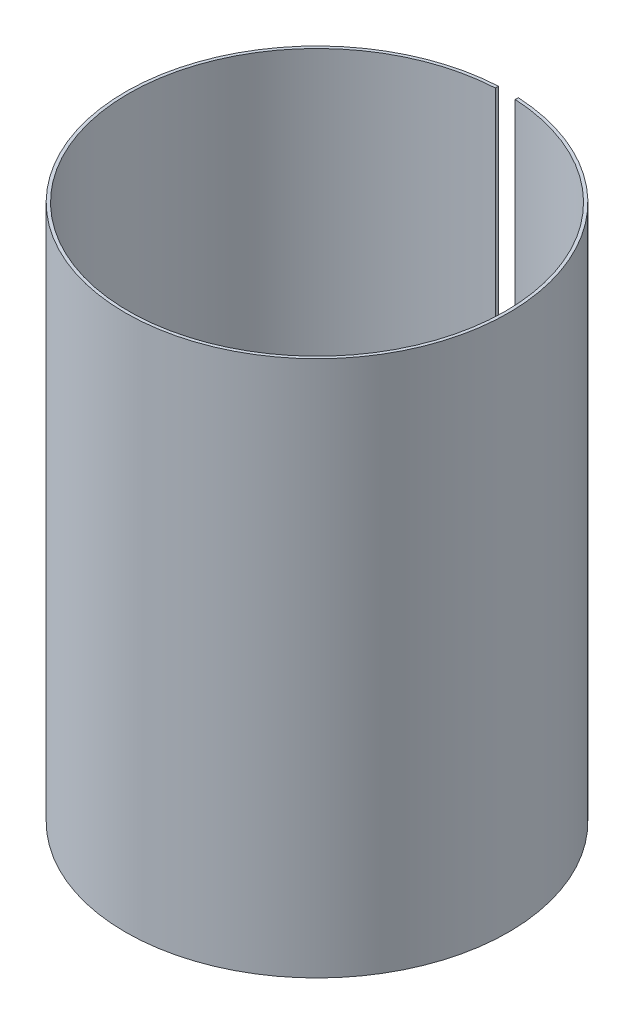
SolidWorks part; units mm, degrees
ref_plane "Front Plane" through (0, 0, 0) normal (0, 0, 1) x (1, 0, 0)
ref_plane "Top Plane" through (0, 0, 0) normal (0, 1, 0) x (1, 0, 0)
ref_plane "Right Plane" through (0, 0, 0) normal (1, 0, 0) x (0, 0, -1)
sketch "Sketch1" plane through (0, 0, 0) normal (0, 1, 0) x (1, 0, 0)
  circle A0 centre (0, 0) radius 62.5
  circle A1 centre (0, 0) radius 61.5
  dimension "D1" = 1
  dimension "D2" = 125
extrude "Boss-Extrude1" add sketch "Sketch1" along normal mid plane 175
sketch "Sketch2" plane through (0, 87.5, 0) normal (0, 1, 0) x (1, 0, 0)
  line L0 (0, 0) -> (0, 76.4001) construction
  line L2 (-3.25, 62.5) -> (3.25, 62.5)
  line L3 (-3.25, 62.5) -> (-3.25, 61.4141)
  line L4 (-3.25, 61.4141) -> (3.25, 61.4141)
  line L5 (3.25, 62.5) -> (3.25, 61.4141)
  circle A0 centre (0, 0) radius 62.5 construction
  circle A1 centre (0, 0) radius 61.5 construction
  point P9 (0, 0)
  dimension "D1" = 6.5
extrude "Cut-Extrude1" cut sketch "Sketch2" against normal through all
